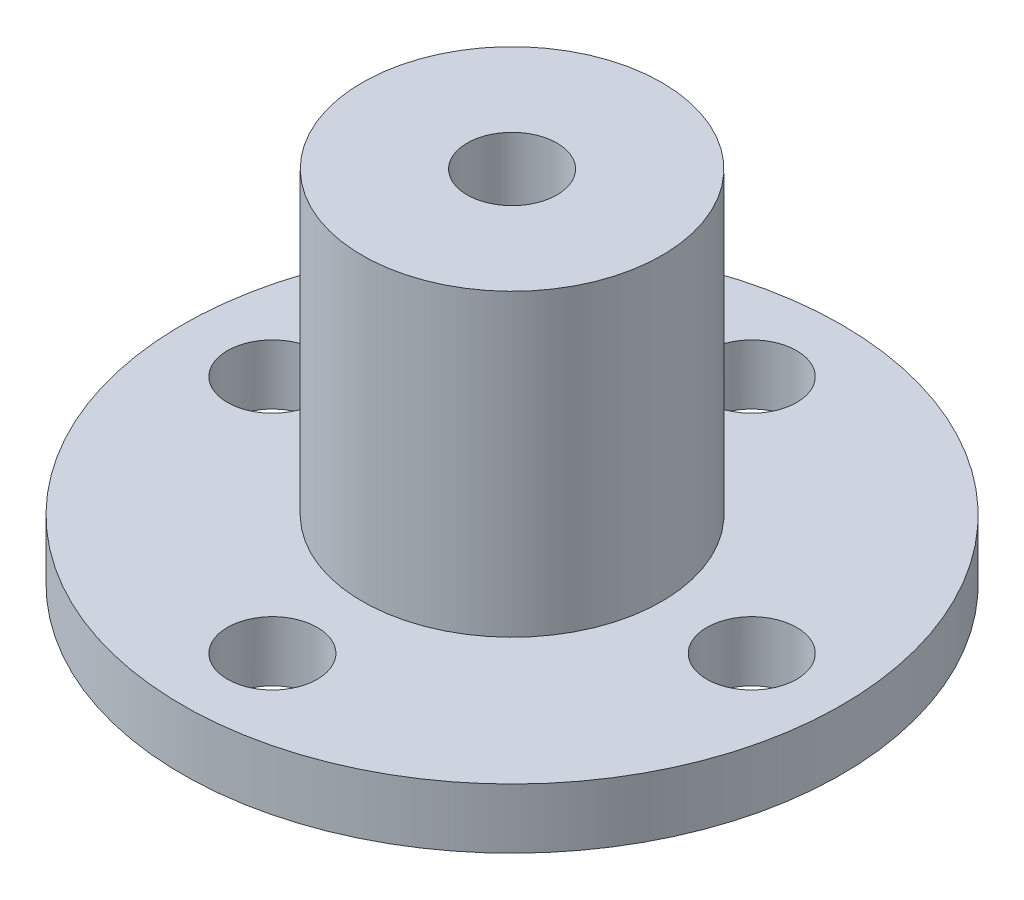
SolidWorks part; units mm, degrees
ref_plane "前视基准面" through (0, 0, 0) normal (0, 0, 1) x (1, 0, 0)
ref_plane "上视基准面" through (0, 0, 0) normal (0, 1, 0) x (1, 0, 0)
ref_plane "右视基准面" through (0, 0, 0) normal (1, 0, 0) x (0, 0, -1)
other "Configuration Table"
sketch "草图1" plane through (0, 0, 0) normal (0, 0, 1) x (1, 0, 0)
  line L0 (0, 0) -> (0, 12)
  line L1 (0, 12) -> (5, 12)
  line L2 (5, 12) -> (5, 2)
  line L3 (5, 2) -> (11, 2)
  line L4 (11, 2) -> (11, 0)
  line L5 (0, 0) -> (11, 0)
  point P6 (6.1405, -0.087)
  dimension "D1" = 2
  dimension "D2" = 12
  dimension "D3" = 5
  dimension "D4" = 11
revolve "旋转1" add sketch "草图1" angle 360 about L0
sketch "草图7" plane through (0, 0, 0) normal (0, -1, 0) x (1, 0, 0)
  circle A0 centre (0, 0) radius 1.5
  dimension "D1" = 3
extrude "切除-拉伸1" cut sketch "草图7" against normal through all
sketch "草图8" plane through (0, 0, 0) normal (0, -1, 0) x (1, 0, 0)
  circle A0 centre (-8, 0) radius 1.5
  circle A1 centre (0, 8) radius 1.5
  circle A2 centre (8, 0) radius 1.5
  circle A3 centre (0, -8) radius 1.5
  point P12 (0, 0)
  dimension "D2" = 3
  dimension "D1" = 8
  dimension "D3" = 4
extrude "切除-拉伸2" cut sketch "草图8" against normal through all
